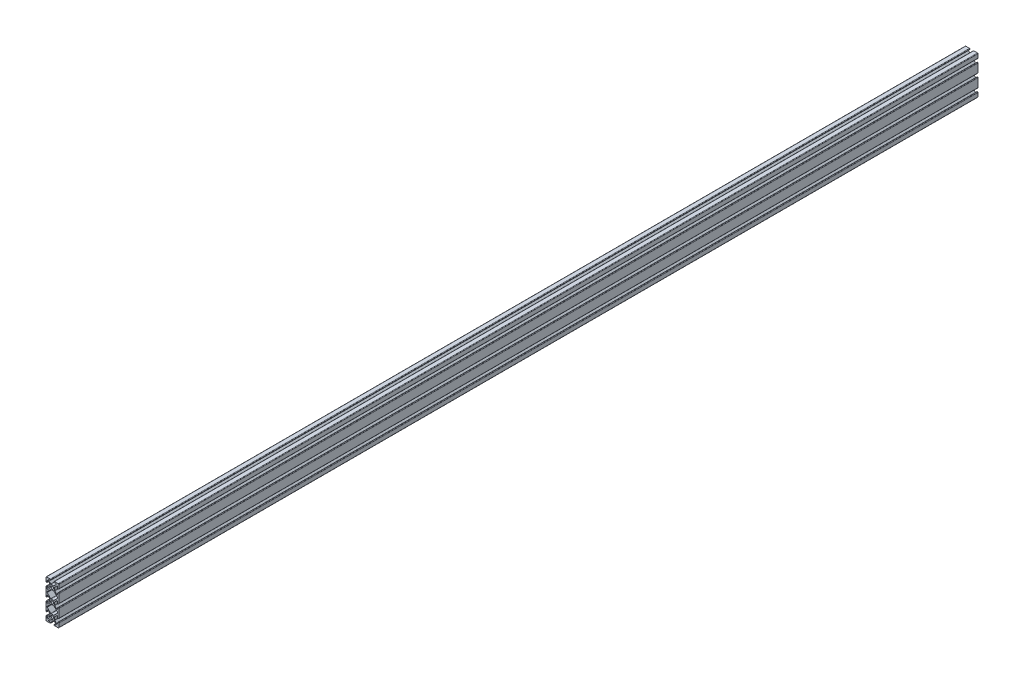
SolidWorks part; units mm, degrees
ref_plane "Front Plane" through (0, 0, 0) normal (0, 0, 1) x (1, 0, 0)
ref_plane "Top Plane" through (0, 0, 0) normal (0, 1, 0) x (1, 0, 0)
ref_plane "Right Plane" through (0, 0, 0) normal (1, 0, 0) x (0, 0, -1)
sketch "Sketch1" plane through (0, 0, 0) normal (0, 0, 1) x (1, 0, 0)
  line L0 (-12.7, 38.1) -> (-12.7, 12.7) construction
  line L1 (-12.7, -38.1) -> (12.7, -38.1) construction
  line L2 (-12.7, 12.7) -> (-12.7, -12.7) construction
  line L3 (-12.7, 38.1) -> (12.7, 38.1) construction
  line L4 (-12.7, -12.7) -> (-12.7, -38.1) construction
  line L5 (-12.7, -38.1) -> (12.7, 38.1) construction
  line L6 (-12.7, 38.1) -> (12.7, -38.1) construction
  line L7 (12.7, 38.1) -> (12.7, 12.7) construction
  line L8 (12.7, 12.7) -> (12.7, -12.7) construction
  line L9 (12.7, -12.7) -> (12.7, -38.1) construction
  line L10 (-12.7, 12.7) -> (12.7, 12.7) construction
  line L11 (-12.7, -12.7) -> (12.7, -12.7) construction
  line L12 (12.7, -12.7) -> (-12.7, -38.1) construction
  line L13 (12.7, -38.1) -> (-12.7, -12.7) construction
  line L14 (0, 38.1) -> (0, -38.1) construction
  line L15 (12.7, 12.7) -> (-12.7, 38.1) construction
  line L16 (12.7, 38.1) -> (-12.7, 12.7) construction
  line L17 (-12.7, 37.084) -> (-12.7, 29.6672)
  line L18 (-11.684, 28.6512) -> (-11.5062, 28.6512)
  line L19 (-10.4902, 29.6672) -> (-10.4902, 31.8748)
  line L20 (-8.7558, 32.5932) -> (-4.8188, 28.6562)
  line L21 (-4.5212, 27.9378) -> (-4.5212, 22.8622)
  line L22 (-4.8188, 22.1438) -> (-8.7558, 18.2068)
  line L23 (-10.4902, 18.9252) -> (-10.4902, 21.1328)
  line L24 (-11.5062, 22.1488) -> (-11.684, 22.1488)
  line L25 (-12.7, 21.1328) -> (-12.7, 4.2672)
  line L26 (-12.7, 0) -> (12.7, 0) construction
  line L27 (-12.7, -25.4) -> (12.7, -25.4) construction
  line L28 (-12.7, 25.4) -> (12.7, 25.4) construction
  line L29 (4.2672, 38.1) -> (11.684, 38.1)
  line L30 (3.2512, 36.9062) -> (3.2512, 37.084)
  line L31 (6.4748, 35.8902) -> (4.2672, 35.8902)
  line L32 (3.2562, 30.2188) -> (7.1932, 34.1558)
  line L33 (-2.5378, 29.9212) -> (2.5378, 29.9212)
  line L34 (-7.1932, 34.1558) -> (-3.2562, 30.2188)
  line L35 (-4.2672, 35.8902) -> (-6.4748, 35.8902)
  line L36 (-3.2512, 37.084) -> (-3.2512, 36.9062)
  line L37 (-11.684, 38.1) -> (-4.2672, 38.1)
  line L38 (4.5212, 2.5378) -> (4.5212, -2.5378)
  line L39 (11.5062, 22.1488) -> (11.684, 22.1488)
  line L40 (10.4902, 18.9252) -> (10.4902, 21.1328)
  line L41 (4.8188, 22.1438) -> (8.7558, 18.2068)
  line L42 (4.5212, 27.9378) -> (4.5212, 22.8622)
  line L43 (8.7558, 32.5932) -> (4.8188, 28.6562)
  line L44 (10.4902, 29.6672) -> (10.4902, 31.8748)
  line L45 (11.684, 28.6512) -> (11.5062, 28.6512)
  line L46 (12.7, 37.084) -> (12.7, 29.6672)
  line L47 (-10.4902, 12.4736) -> (-10.4902, 12.9264)
  line L48 (-10.1926, 13.6448) -> (-3.2562, 20.5812)
  line L49 (-2.5378, 20.8788) -> (2.5378, 20.8788)
  line L50 (10.4902, 12.4736) -> (10.4902, 12.9264)
  line L51 (10.1926, 13.6448) -> (3.2562, 20.5812)
  line L52 (10.1926, 11.7552) -> (3.2562, 4.8188)
  line L53 (-2.5378, 4.5212) -> (2.5378, 4.5212)
  line L54 (-10.1926, 11.7552) -> (-3.2562, 4.8188)
  line L55 (-2.5378, -4.5212) -> (2.5378, -4.5212)
  line L56 (-10.1926, -11.7552) -> (-3.2562, -4.8188)
  line L57 (10.1926, -11.7552) -> (3.2562, -4.8188)
  line L58 (10.4902, -12.4736) -> (10.4902, -12.9264)
  line L59 (10.1926, -13.6448) -> (3.2562, -20.5812)
  line L60 (-2.5378, -20.8788) -> (2.5378, -20.8788)
  line L61 (-10.1926, -13.6448) -> (-3.2562, -20.5812)
  line L62 (-10.4902, -12.4736) -> (-10.4902, -12.9264)
  line L63 (4.8188, -3.2562) -> (8.7558, -7.1932)
  line L64 (11.5062, -22.1488) -> (11.684, -22.1488)
  line L65 (10.4902, -18.9252) -> (10.4902, -21.1328)
  line L66 (4.8188, -22.1438) -> (8.7558, -18.2068)
  line L67 (4.5212, -27.9378) -> (4.5212, -22.8622)
  line L68 (8.7558, -32.5932) -> (4.8188, -28.6562)
  line L69 (10.4902, -29.6672) -> (10.4902, -31.8748)
  line L70 (11.684, -28.6512) -> (11.5062, -28.6512)
  line L71 (12.7, -37.084) -> (12.7, -29.6672)
  line L72 (3.2512, -36.9062) -> (3.2512, -37.084)
  line L73 (6.4748, -35.8902) -> (4.2672, -35.8902)
  line L74 (3.2562, -30.2188) -> (7.1932, -34.1558)
  line L75 (-2.5378, -29.9212) -> (2.5378, -29.9212)
  line L76 (-7.1932, -34.1558) -> (-3.2562, -30.2188)
  line L77 (-4.2672, -35.8902) -> (-6.4748, -35.8902)
  line L78 (-3.2512, -37.084) -> (-3.2512, -36.9062)
  line L79 (-11.684, -38.1) -> (-4.2672, -38.1)
  line L80 (4.2672, -38.1) -> (11.684, -38.1)
  line L81 (4.8188, 3.2562) -> (8.7558, 7.1932)
  line L82 (-11.5062, -22.1488) -> (-11.684, -22.1488)
  line L83 (-10.4902, -18.9252) -> (-10.4902, -21.1328)
  line L84 (-4.8188, -22.1438) -> (-8.7558, -18.2068)
  line L85 (-4.5212, -27.9378) -> (-4.5212, -22.8622)
  line L86 (-8.7558, -32.5932) -> (-4.8188, -28.6562)
  line L87 (-10.4902, -29.6672) -> (-10.4902, -31.8748)
  line L88 (-11.684, -28.6512) -> (-11.5062, -28.6512)
  line L89 (-12.7, -37.084) -> (-12.7, -29.6672)
  line L90 (-4.8188, 3.2562) -> (-8.7558, 7.1932)
  line L91 (-10.4902, 6.4748) -> (-10.4902, 4.2672)
  line L92 (-11.5062, 3.2512) -> (-11.684, 3.2512)
  line L93 (-4.5212, 2.5378) -> (-4.5212, -2.5378)
  line L94 (-12.7, -21.1328) -> (-12.7, -4.2672)
  line L95 (-4.8188, -3.2562) -> (-8.7558, -7.1932)
  line L96 (-10.4902, -6.4748) -> (-10.4902, -4.2672)
  line L97 (-11.5062, -3.2512) -> (-11.684, -3.2512)
  line L98 (10.4902, -6.4748) -> (10.4902, -4.2672)
  line L99 (10.4902, 6.4748) -> (10.4902, 4.2672)
  line L100 (11.5062, 3.2512) -> (11.684, 3.2512)
  line L101 (11.5062, -3.2512) -> (11.684, -3.2512)
  line L102 (12.7, -21.1328) -> (12.7, -4.2672)
  line L103 (12.7, 21.1328) -> (12.7, 4.2672)
  circle A0 centre (0, 25.4) radius 2.6035
  circle A1 centre (0, 0) radius 2.6035
  circle A2 centre (0, -25.4) radius 2.6035
  arc A3 (-12.7, 21.1328) -> (-11.684, 22.1488) centre (-11.684, 21.1328) cw
  arc A4 (-11.5062, 22.1488) -> (-10.4902, 21.1328) centre (-11.5062, 21.1328) cw
  arc A5 (-10.4902, 18.9252) -> (-8.7558, 18.2068) centre (-9.4742, 18.9252) ccw
  arc A6 (-4.8188, 22.1438) -> (-4.5212, 22.8622) centre (-5.5372, 22.8622) ccw
  arc A7 (-4.5212, 27.9378) -> (-4.8188, 28.6562) centre (-5.5372, 27.9378) ccw
  arc A8 (-8.7558, 32.5932) -> (-10.4902, 31.8748) centre (-9.4742, 31.8748) ccw
  arc A9 (-10.4902, 29.6672) -> (-11.5062, 28.6512) centre (-11.5062, 29.6672) cw
  arc A10 (-11.684, 28.6512) -> (-12.7, 29.6672) centre (-11.684, 29.6672) cw
  arc A11 (4.2672, 38.1) -> (3.2512, 37.084) centre (4.2672, 37.084) ccw
  arc A12 (3.2512, 36.9062) -> (4.2672, 35.8902) centre (4.2672, 36.9062) ccw
  arc A13 (6.4748, 35.8902) -> (7.1932, 34.1558) centre (6.4748, 34.8742) cw
  arc A14 (3.2562, 30.2188) -> (2.5378, 29.9212) centre (2.5378, 30.9372) cw
  arc A15 (-2.5378, 29.9212) -> (-3.2562, 30.2188) centre (-2.5378, 30.9372) cw
  arc A16 (-7.1932, 34.1558) -> (-6.4748, 35.8902) centre (-6.4748, 34.8742) cw
  arc A17 (-4.2672, 35.8902) -> (-3.2512, 36.9062) centre (-4.2672, 36.9062) ccw
  arc A18 (-3.2512, 37.084) -> (-4.2672, 38.1) centre (-4.2672, 37.084) ccw
  arc A19 (12.7, 21.1328) -> (11.684, 22.1488) centre (11.684, 21.1328) ccw
  arc A20 (11.5062, 22.1488) -> (10.4902, 21.1328) centre (11.5062, 21.1328) ccw
  arc A21 (10.4902, 18.9252) -> (8.7558, 18.2068) centre (9.4742, 18.9252) cw
  arc A22 (4.8188, 22.1438) -> (4.5212, 22.8622) centre (5.5372, 22.8622) cw
  arc A23 (4.5212, 27.9378) -> (4.8188, 28.6562) centre (5.5372, 27.9378) cw
  arc A24 (8.7558, 32.5932) -> (10.4902, 31.8748) centre (9.4742, 31.8748) cw
  arc A25 (10.4902, 29.6672) -> (11.5062, 28.6512) centre (11.5062, 29.6672) ccw
  arc A26 (11.684, 28.6512) -> (12.7, 29.6672) centre (11.684, 29.6672) ccw
  arc A27 (12.7, 37.084) -> (11.684, 38.1) centre (11.684, 37.084) ccw
  arc A28 (-11.684, 38.1) -> (-12.7, 37.084) centre (-11.684, 37.084) ccw
  arc A29 (-10.1926, 13.6448) -> (-10.4902, 12.9264) centre (-9.4742, 12.9264) ccw
  arc A30 (-2.5378, 20.8788) -> (-3.2562, 20.5812) centre (-2.5378, 19.8628) ccw
  arc A31 (10.1926, 13.6448) -> (10.4902, 12.9264) centre (9.4742, 12.9264) cw
  arc A32 (2.5378, 20.8788) -> (3.2562, 20.5812) centre (2.5378, 19.8628) cw
  arc A33 (10.1926, 11.7552) -> (10.4902, 12.4736) centre (9.4742, 12.4736) ccw
  arc A34 (2.5378, 4.5212) -> (3.2562, 4.8188) centre (2.5378, 5.5372) ccw
  arc A35 (-2.5378, 4.5212) -> (-3.2562, 4.8188) centre (-2.5378, 5.5372) cw
  arc A36 (-10.1926, 11.7552) -> (-10.4902, 12.4736) centre (-9.4742, 12.4736) cw
  arc A37 (2.5378, -4.5212) -> (3.2562, -4.8188) centre (2.5378, -5.5372) cw
  arc A38 (-2.5378, -4.5212) -> (-3.2562, -4.8188) centre (-2.5378, -5.5372) ccw
  arc A39 (10.1926, -11.7552) -> (10.4902, -12.4736) centre (9.4742, -12.4736) cw
  arc A40 (10.1926, -13.6448) -> (10.4902, -12.9264) centre (9.4742, -12.9264) ccw
  arc A41 (2.5378, -20.8788) -> (3.2562, -20.5812) centre (2.5378, -19.8628) ccw
  arc A42 (-2.5378, -20.8788) -> (-3.2562, -20.5812) centre (-2.5378, -19.8628) cw
  arc A43 (-10.1926, -13.6448) -> (-10.4902, -12.9264) centre (-9.4742, -12.9264) cw
  arc A44 (-10.1926, -11.7552) -> (-10.4902, -12.4736) centre (-9.4742, -12.4736) ccw
  arc A45 (12.7, -21.1328) -> (11.684, -22.1488) centre (11.684, -21.1328) cw
  arc A46 (11.5062, -22.1488) -> (10.4902, -21.1328) centre (11.5062, -21.1328) cw
  arc A47 (10.4902, -18.9252) -> (8.7558, -18.2068) centre (9.4742, -18.9252) ccw
  arc A48 (4.8188, -22.1438) -> (4.5212, -22.8622) centre (5.5372, -22.8622) ccw
  arc A49 (4.5212, -27.9378) -> (4.8188, -28.6562) centre (5.5372, -27.9378) ccw
  arc A50 (8.7558, -32.5932) -> (10.4902, -31.8748) centre (9.4742, -31.8748) ccw
  arc A51 (10.4902, -29.6672) -> (11.5062, -28.6512) centre (11.5062, -29.6672) cw
  arc A52 (11.684, -28.6512) -> (12.7, -29.6672) centre (11.684, -29.6672) cw
  arc A53 (4.2672, -38.1) -> (3.2512, -37.084) centre (4.2672, -37.084) cw
  arc A54 (3.2512, -36.9062) -> (4.2672, -35.8902) centre (4.2672, -36.9062) cw
  arc A55 (6.4748, -35.8902) -> (7.1932, -34.1558) centre (6.4748, -34.8742) ccw
  arc A56 (3.2562, -30.2188) -> (2.5378, -29.9212) centre (2.5378, -30.9372) ccw
  arc A57 (-2.5378, -29.9212) -> (-3.2562, -30.2188) centre (-2.5378, -30.9372) ccw
  arc A58 (-7.1932, -34.1558) -> (-6.4748, -35.8902) centre (-6.4748, -34.8742) ccw
  arc A59 (-4.2672, -35.8902) -> (-3.2512, -36.9062) centre (-4.2672, -36.9062) cw
  arc A60 (-3.2512, -37.084) -> (-4.2672, -38.1) centre (-4.2672, -37.084) cw
  arc A61 (12.7, -37.084) -> (11.684, -38.1) centre (11.684, -37.084) cw
  arc A62 (-12.7, -21.1328) -> (-11.684, -22.1488) centre (-11.684, -21.1328) ccw
  arc A63 (-11.5062, -22.1488) -> (-10.4902, -21.1328) centre (-11.5062, -21.1328) ccw
  arc A64 (-10.4902, -18.9252) -> (-8.7558, -18.2068) centre (-9.4742, -18.9252) cw
  arc A65 (-4.8188, -22.1438) -> (-4.5212, -22.8622) centre (-5.5372, -22.8622) cw
  arc A66 (-4.5212, -27.9378) -> (-4.8188, -28.6562) centre (-5.5372, -27.9378) cw
  arc A67 (-8.7558, -32.5932) -> (-10.4902, -31.8748) centre (-9.4742, -31.8748) cw
  arc A68 (-10.4902, -29.6672) -> (-11.5062, -28.6512) centre (-11.5062, -29.6672) ccw
  arc A69 (-11.684, -28.6512) -> (-12.7, -29.6672) centre (-11.684, -29.6672) ccw
  arc A70 (-11.684, -38.1) -> (-12.7, -37.084) centre (-11.684, -37.084) cw
  arc A71 (-4.8188, 3.2562) -> (-4.5212, 2.5378) centre (-5.5372, 2.5378) cw
  arc A72 (-10.4902, 6.4748) -> (-8.7558, 7.1932) centre (-9.4742, 6.4748) cw
  arc A73 (-11.5062, 3.2512) -> (-10.4902, 4.2672) centre (-11.5062, 4.2672) ccw
  arc A74 (-12.7, 4.2672) -> (-11.684, 3.2512) centre (-11.684, 4.2672) ccw
  arc A75 (-4.8188, -3.2562) -> (-4.5212, -2.5378) centre (-5.5372, -2.5378) ccw
  arc A76 (-10.4902, -6.4748) -> (-8.7558, -7.1932) centre (-9.4742, -6.4748) ccw
  arc A77 (-11.5062, -3.2512) -> (-10.4902, -4.2672) centre (-11.5062, -4.2672) cw
  arc A78 (-12.7, -4.2672) -> (-11.684, -3.2512) centre (-11.684, -4.2672) cw
  arc A79 (4.8188, 3.2562) -> (4.5212, 2.5378) centre (5.5372, 2.5378) ccw
  arc A80 (4.8188, -3.2562) -> (4.5212, -2.5378) centre (5.5372, -2.5378) cw
  arc A81 (10.4902, 6.4748) -> (8.7558, 7.1932) centre (9.4742, 6.4748) ccw
  arc A82 (10.4902, -6.4748) -> (8.7558, -7.1932) centre (9.4742, -6.4748) cw
  arc A83 (11.5062, -3.2512) -> (10.4902, -4.2672) centre (11.5062, -4.2672) ccw
  arc A84 (11.5062, 3.2512) -> (10.4902, 4.2672) centre (11.5062, 4.2672) cw
  arc A85 (12.7, -4.2672) -> (11.684, -3.2512) centre (11.684, -4.2672) ccw
  arc A86 (12.7, 4.2672) -> (11.684, 3.2512) centre (11.684, 4.2672) cw
  point P0 (0, 0)
  point P26 (-12.7, 22.1488)
  point P41 (-12.7, 28.6512)
  point P107 (-6.7244, 17.113)
  point P120 (0, 20.8788)
  point P121 (10.4902, 12.7)
  point P132 (-10.4902, 12.7)
  point P249 (-4.5212, 0)
  dimension "D2" = 5.207
  dimension "D8" = 1.016
  dimension "D9" = 3.2512
  dimension "D10" = 1.1049
  dimension "D1" = 25.4
  dimension "D3" = 2.2098
  dimension "D4" = 6.5024
  dimension "D5" = 4.5212
  dimension "D6" = 1.1049
  dimension "D7" = 1.1049
  dimension "D11" = 4.5212
extrude "Main Extrusion" add sketch "Sketch1" along normal mid plane 1828.8
sketch "Sketch2" plane through (0, 0, 914.4) normal (0, 0, 1) x (1, 0, 0)
  line L0 (-4.2672, 38.1) -> (-11.684, 38.1) construction
  line L1 (-12.7, -38.1) -> (12.7, -38.1) construction
  line L2 (-12.7, 38.1) -> (-12.7, 12.7) construction
  line L3 (-12.7, 38.1) -> (12.7, 38.1) construction
  line L4 (-12.7, 21.1328) -> (-12.7, 4.2672) construction
  line L5 (-12.7, -38.1) -> (12.7, 38.1) construction
  line L6 (-12.7, 38.1) -> (12.7, -38.1) construction
  line L7 (-12.7, 12.7) -> (-12.7, -12.7) construction
  line L8 (0, 38.1) -> (0, -38.1) construction
  line L9 (-12.7, -4.2672) -> (-12.7, -21.1328) construction
  line L10 (-12.7, -12.7) -> (-12.7, -38.1) construction
  line L11 (12.7, 38.1) -> (12.7, 12.7) construction
  line L12 (12.7, 4.2672) -> (12.7, 21.1328) construction
  line L13 (12.7, 12.7) -> (12.7, -12.7) construction
  line L14 (12.7, -21.1328) -> (12.7, -4.2672) construction
  line L15 (12.7, -12.7) -> (12.7, -38.1) construction
  line L16 (-12.7, 25.4) -> (12.7, 25.4) construction
  line L17 (-12.7, 0) -> (12.7, 0) construction
  line L18 (-12.7, -25.4) -> (12.7, -25.4) construction
  line L19 (-12.7, 12.7) -> (12.7, 12.7) construction
  line L20 (-12.7, -12.7) -> (12.7, -12.7) construction
  line L21 (-3.2512, 36.9062) -> (-3.2512, 37.084) construction
  line L22 (-10.4902, 38.1) -> (-9.4742, 38.1)
  line L23 (-6.477, 38.1) -> (-5.461, 38.1)
  line L24 (-12.7, 38.1) -> (12.7, 12.7) construction
  line L25 (12.7, 12.7) -> (-12.7, -12.7) construction
  line L26 (-12.7, -12.7) -> (12.7, -38.1) construction
  line L27 (-12.7, -38.1) -> (12.7, -12.7) construction
  line L28 (12.7, -12.7) -> (-12.7, 12.7) construction
  line L29 (-12.7, 12.7) -> (12.7, 38.1) construction
  line L30 (6.477, 38.1) -> (5.461, 38.1)
  line L31 (10.4902, 38.1) -> (9.4742, 38.1)
  line L32 (-12.7, 14.9098) -> (-12.7, 15.9258)
  line L33 (-12.7, 18.923) -> (-12.7, 19.939)
  line L34 (-12.7, 31.877) -> (-12.7, 30.861)
  line L35 (-12.7, 35.8902) -> (-12.7, 34.8742)
  line L36 (12.7, 35.8902) -> (12.7, 34.8742)
  line L37 (12.7, 31.877) -> (12.7, 30.861)
  line L38 (12.7, 18.923) -> (12.7, 19.939)
  line L39 (12.7, 14.9098) -> (12.7, 15.9258)
  line L40 (12.7, 10.4902) -> (12.7, 9.4742)
  line L41 (12.7, 6.477) -> (12.7, 5.461)
  line L42 (-12.7, 10.4902) -> (-12.7, 9.4742)
  line L43 (-12.7, 6.477) -> (-12.7, 5.461)
  line L44 (12.7, -6.477) -> (12.7, -5.461)
  line L45 (12.7, -10.4902) -> (12.7, -9.4742)
  line L46 (12.7, -14.9098) -> (12.7, -15.9258)
  line L47 (12.7, -18.923) -> (12.7, -19.939)
  line L48 (12.7, -31.877) -> (12.7, -30.861)
  line L49 (12.7, -35.8902) -> (12.7, -34.8742)
  line L50 (10.4902, -38.1) -> (9.4742, -38.1)
  line L51 (6.477, -38.1) -> (5.461, -38.1)
  line L52 (-6.477, -38.1) -> (-5.461, -38.1)
  line L53 (-10.4902, -38.1) -> (-9.4742, -38.1)
  line L54 (-12.7, -35.8902) -> (-12.7, -34.8742)
  line L55 (-12.7, -31.877) -> (-12.7, -30.861)
  line L56 (-12.7, -18.923) -> (-12.7, -19.939)
  line L57 (-12.7, -14.9098) -> (-12.7, -15.9258)
  line L58 (-12.7, -10.4902) -> (-12.7, -9.4742)
  line L59 (-12.7, -6.477) -> (-12.7, -5.461)
  arc A0 (-10.4902, 38.1) -> (-9.4742, 38.1) centre (-9.9822, 38.1) ccw
  arc A1 (-6.477, 38.1) -> (-5.461, 38.1) centre (-5.969, 38.1) ccw
  arc A2 (6.477, 38.1) -> (5.461, 38.1) centre (5.969, 38.1) cw
  arc A3 (10.4902, 38.1) -> (9.4742, 38.1) centre (9.9822, 38.1) cw
  arc A4 (-12.7, 14.9098) -> (-12.7, 15.9258) centre (-12.7, 15.4178) ccw
  arc A5 (-12.7, 18.923) -> (-12.7, 19.939) centre (-12.7, 19.431) ccw
  arc A6 (-12.7, 31.877) -> (-12.7, 30.861) centre (-12.7, 31.369) cw
  arc A7 (-12.7, 35.8902) -> (-12.7, 34.8742) centre (-12.7, 35.3822) cw
  arc A8 (12.7, 35.8902) -> (12.7, 34.8742) centre (12.7, 35.3822) ccw
  arc A9 (12.7, 31.877) -> (12.7, 30.861) centre (12.7, 31.369) ccw
  arc A10 (12.7, 18.923) -> (12.7, 19.939) centre (12.7, 19.431) cw
  arc A11 (12.7, 14.9098) -> (12.7, 15.9258) centre (12.7, 15.4178) cw
  arc A12 (12.7, 10.4902) -> (12.7, 9.4742) centre (12.7, 9.9822) ccw
  arc A13 (12.7, 6.477) -> (12.7, 5.461) centre (12.7, 5.969) ccw
  arc A14 (-12.7, 10.4902) -> (-12.7, 9.4742) centre (-12.7, 9.9822) cw
  arc A15 (-12.7, 6.477) -> (-12.7, 5.461) centre (-12.7, 5.969) cw
  arc A16 (12.7, -6.477) -> (12.7, -5.461) centre (12.7, -5.969) cw
  arc A17 (12.7, -10.4902) -> (12.7, -9.4742) centre (12.7, -9.9822) cw
  arc A18 (12.7, -14.9098) -> (12.7, -15.9258) centre (12.7, -15.4178) ccw
  arc A19 (12.7, -18.923) -> (12.7, -19.939) centre (12.7, -19.431) ccw
  arc A20 (12.7, -31.877) -> (12.7, -30.861) centre (12.7, -31.369) cw
  arc A21 (12.7, -35.8902) -> (12.7, -34.8742) centre (12.7, -35.3822) cw
  arc A22 (10.4902, -38.1) -> (9.4742, -38.1) centre (9.9822, -38.1) ccw
  arc A23 (6.477, -38.1) -> (5.461, -38.1) centre (5.969, -38.1) ccw
  arc A24 (-6.477, -38.1) -> (-5.461, -38.1) centre (-5.969, -38.1) cw
  arc A25 (-10.4902, -38.1) -> (-9.4742, -38.1) centre (-9.9822, -38.1) cw
  arc A26 (-12.7, -35.8902) -> (-12.7, -34.8742) centre (-12.7, -35.3822) ccw
  arc A27 (-12.7, -31.877) -> (-12.7, -30.861) centre (-12.7, -31.369) ccw
  arc A28 (-12.7, -18.923) -> (-12.7, -19.939) centre (-12.7, -19.431) cw
  arc A29 (-12.7, -14.9098) -> (-12.7, -15.9258) centre (-12.7, -15.4178) cw
  arc A30 (-12.7, -10.4902) -> (-12.7, -9.4742) centre (-12.7, -9.9822) ccw
  arc A31 (-12.7, -6.477) -> (-12.7, -5.461) centre (-12.7, -5.969) ccw
  point P0 (0, 0)
  dimension "D1" = 0.508
  dimension "D2" = 2.2098
  dimension "D3" = 2.2098
